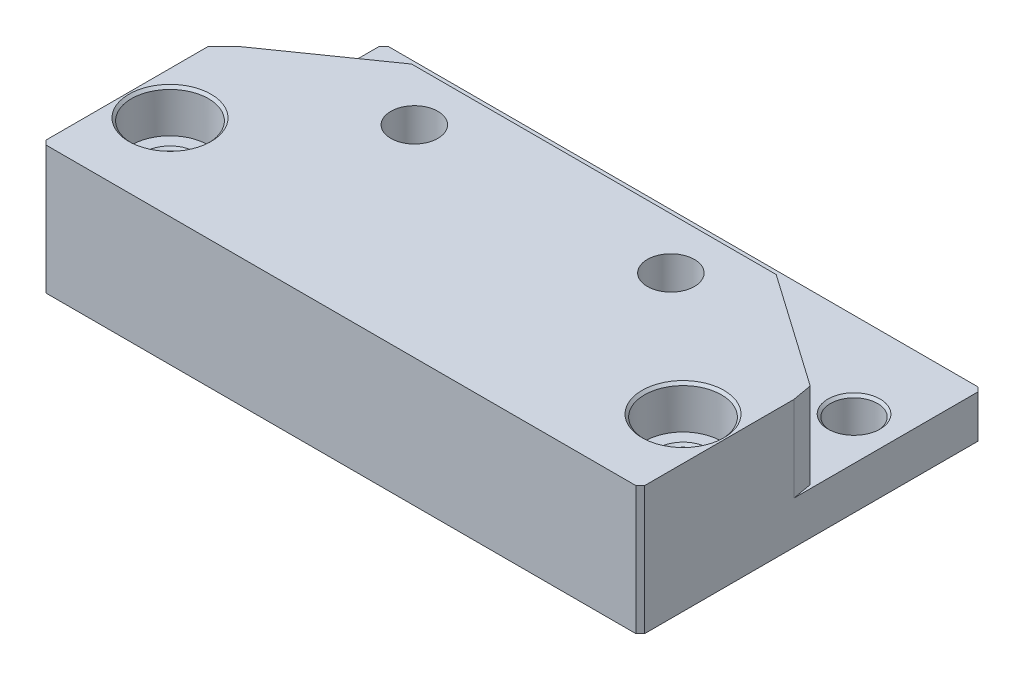
SolidWorks part; units mm, degrees
ref_plane "Front Plane" through (0, 0, 0) normal (0, 0, 1) x (1, 0, 0)
ref_plane "Top Plane" through (0, 0, 0) normal (0, 1, 0) x (1, 0, 0)
ref_plane "Right Plane" through (0, 0, 0) normal (1, 0, 0) x (0, 0, -1)
sketch "Sketch1" plane through (0, 0, 0) normal (0, 0, 1) x (1, 0, 0)
  line L1 (-35, -7.5) -> (35, -7.5)
  line L2 (-35, -7.5) -> (-35, 7.5)
  line L3 (-35, 7.5) -> (35, 7.5)
  line L4 (35, -7.5) -> (35, 7.5)
  line L5 (-35, -7.5) -> (35, 7.5) construction
  line L6 (-35, 7.5) -> (35, -7.5) construction
  point P0 (0, 0)
  dimension "D1" = 15
  dimension "D2" = 70
extrude "Boss-Extrude1" add sketch "Sketch1" along normal blind 40
sketch "Sketch2" plane through (0, 7.5, 0) normal (0, 1, 0) x (1, 0, 0)
  line L0 (0, 0) -> (0, -40) construction
  line L2 (35, 0) -> (-35, 0) construction
  circle A0 centre (-15, -16.42) radius 2.75
  circle A1 centre (15, -16.42) radius 2.75
  dimension "D2" = 5.5
  dimension "D3" = 30
  dimension "D1" = 16.42
extrude "Cut-Extrude1" cut sketch "Sketch2" against normal through all
sketch "Sketch3" plane through (0, 7.5, 0) normal (0, 1, 0) x (1, 0, 0)
  line L0 (-35, -10) -> (35, -10) construction
  line L3 (-35, -30) -> (35, -30) construction
  line L6 (35, 0) -> (-35, 0) construction
  line L7 (35, -40) -> (-35, -40) construction
  line L8 (-35, -40) -> (-35, 0) construction
  line L9 (0, -55) -> (0, 55) construction
  circle A0 centre (-30, -10) radius 2.75
  circle A1 centre (30, -10) radius 2.75
  circle A2 centre (-30, -30) radius 2.75
  circle A3 centre (30, -30) radius 2.75
  dimension "D3" = 5.5
  dimension "D4" = 5
  dimension "D6" = 5.5
  dimension "D1" = 10
  dimension "D2" = 10
  dimension "D5" = 5
extrude "Cut-Extrude2" cut sketch "Sketch3" against normal through all
sketch "Sketch7" plane through (0, 7.5, 0) normal (0, 1, 0) x (1, 0, 0)
  line L0 (-30, -10.42) -> (30, -10.42) construction
  line L1 (35, -40) -> (35, 0) construction
  line L2 (-35, 0) -> (35, 0)
  line L5 (35, 0) -> (35, -10.42)
  line L6 (-35, -20) -> (-21.3183, -10.42)
  line L7 (-35, -40) -> (-35, 0) construction
  line L8 (35, -20) -> (21.3183, -10.42)
  line L11 (35, -20) -> (35, -10.42)
  line L12 (21.3183, -10.42) -> (-21.3183, -10.42)
  line L13 (-35, 0) -> (-35, -20)
  dimension "D1" = 6
  dimension "D2" = 55
  dimension "D3" = 55
extrude "Cut-Extrude5" cut sketch "Sketch7" against normal blind 10
sketch "Sketch4" plane through (0, 7.5, 0) normal (0, 1, 0) x (1, 0, 0)
  circle A0 centre (-30, -10) radius 4.5
  circle A1 centre (-30, -30) radius 4.5
  circle A2 centre (30, -30) radius 4.5
  circle A3 centre (30, -10) radius 4.5
  dimension "D1" = 9
extrude "Cut-Extrude3" cut sketch "Sketch4" against normal blind 5
sketch "Sketch5" plane through (0, -7.5, 0) normal (0, -1, 0) x (1, 0, 0)
  circle A0 centre (-15, 16.42) radius 4.5
  circle A1 centre (15, 16.42) radius 4.5
  dimension "D1" = 9
extrude "Cut-Extrude4" cut sketch "Sketch5" against normal blind 5
chamfer "Chamfer1" distance 0.3 angle 45 4 edges at (-30, 2.5, 32.75) (30, 2.5, 32.75) (30, -2.5, 7.25) (-30, -2.5, 7.25)
chamfer "Chamfer2" distance 0.3 angle 45 2 edges at (30, 7.5, 34.5) (-30, 7.5, 34.5)
chamfer "Chamfer3" distance 0.5 angle 45 6 edges at (35, 0, 40) (-35, 0, 40) (-35, 2.5, 20) (-35, -5, 0) (35, -5, 0) (35, 2.5, 20)
